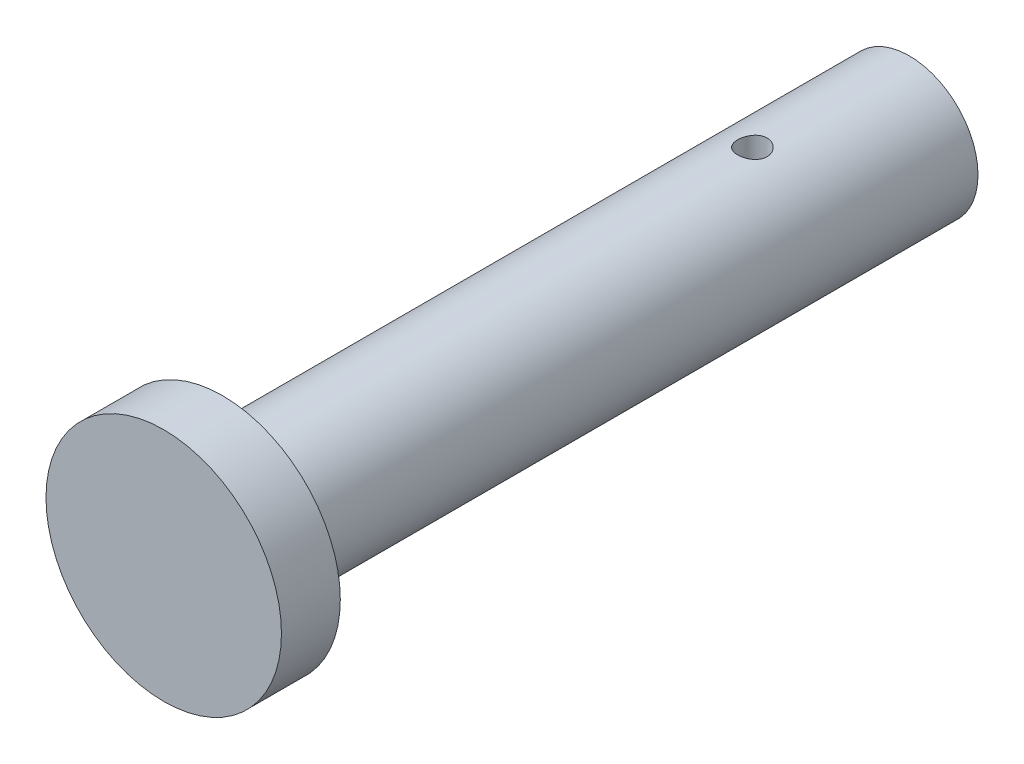
SolidWorks part; units mm, degrees
ref_plane "Front Plane" through (0, 0, 0) normal (0, 0, 1) x (1, 0, 0)
ref_plane "Top Plane" through (0, 0, 0) normal (0, 1, 0) x (1, 0, 0)
ref_plane "Right Plane" through (0, 0, 0) normal (1, 0, 0) x (0, 0, -1)
sketch "Sketch1" plane through (0, 0, 0) normal (0, 0, 1) x (1, 0, 0)
  circle A0 centre (0, 0) radius 3.5
  dimension "D1" = 7
extrude "Boss-Extrude1" add sketch "Sketch1" along normal blind 35
sketch "Sketch3" plane through (0, 0, 0) normal (0, 1, 0) x (1, 0, 0)
  line L1 (-3.5, -35) -> (3.5, -35) construction
  circle A0 centre (0, -8) radius 0.75
  dimension "D2" = 1.5
  dimension "D1" = 27
extrude "Cut-Extrude1" cut sketch "Sketch3" against normal blind 20 from offset 10
sketch "Sketch4" plane through (0, 0, 35) normal (0, 0, 1) x (1, 0, 0)
  circle A0 centre (0, 0) radius 6
  dimension "D1" = 12
extrude "Boss-Extrude2" add sketch "Sketch4" along normal blind 3
